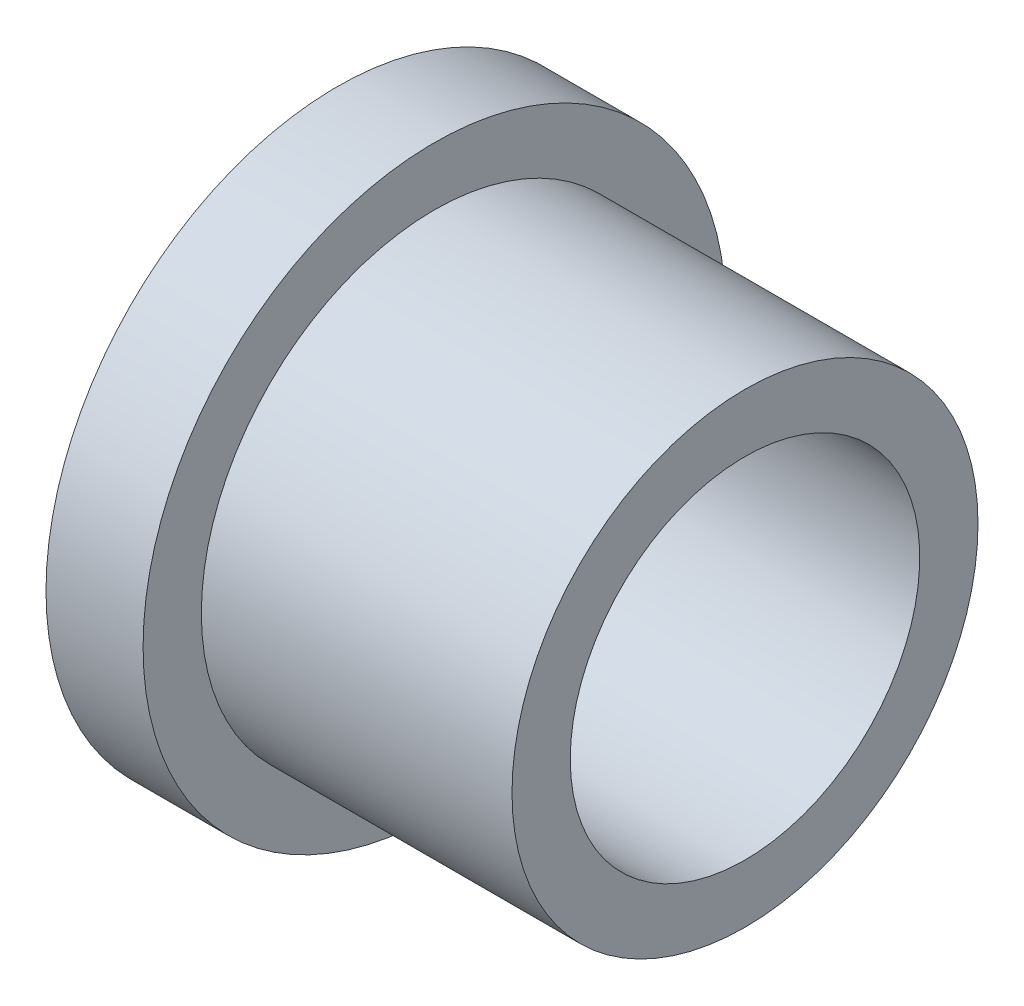
SolidWorks part; units mm, degrees
ref_plane "Front Plane" through (0, 0, 0) normal (0, 0, 1) x (1, 0, 0)
ref_plane "Top Plane" through (0, 0, 0) normal (0, 1, 0) x (1, 0, 0)
ref_plane "Right Plane" through (0, 0, 0) normal (1, 0, 0) x (0, 0, -1)
sketch "Sketch1" plane through (0, 0, 0) normal (0, 0, 1) x (1, 0, 0)
  line L0 (0, 0) -> (13.3636, 0) construction
  line L1 (0, 9) -> (0, 15)
  line L2 (0, 15) -> (5, 15)
  line L3 (5, 15) -> (5, 12)
  line L4 (5, 12) -> (21, 12)
  line L5 (21, 12) -> (21, 9)
  line L6 (21, 9) -> (0, 9)
  dimension "D1" = 21
  dimension "D2" = 16
  dimension "D3" = 3
  dimension "D4" = 6
  dimension "D5" = 12
  dimension "D6" = 21
  dimension "D7" = 5
revolve "Revolve1" add sketch "Sketch1" angle 360 about L0
